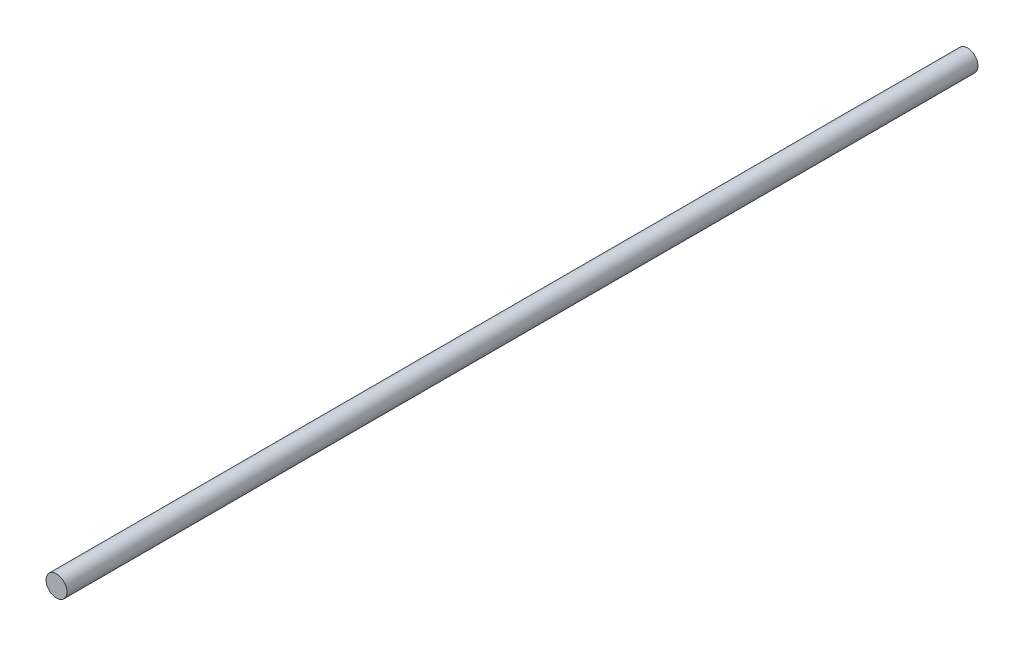
SolidWorks part; units mm, degrees
ref_plane "정면" through (0, 0, 0) normal (0, 0, 1) x (1, 0, 0)
ref_plane "윗면" through (0, 0, 0) normal (0, 1, 0) x (1, 0, 0)
ref_plane "우측면" through (0, 0, 0) normal (1, 0, 0) x (0, 0, -1)
sketch "스케치1" plane through (0, 0, 0) normal (0, 0, 1) x (1, 0, 0)
  circle A0 centre (0, 0) radius 3
  dimension "D1" = 6
extrude "보스-돌출1" add sketch "스케치1" along normal blind 260
